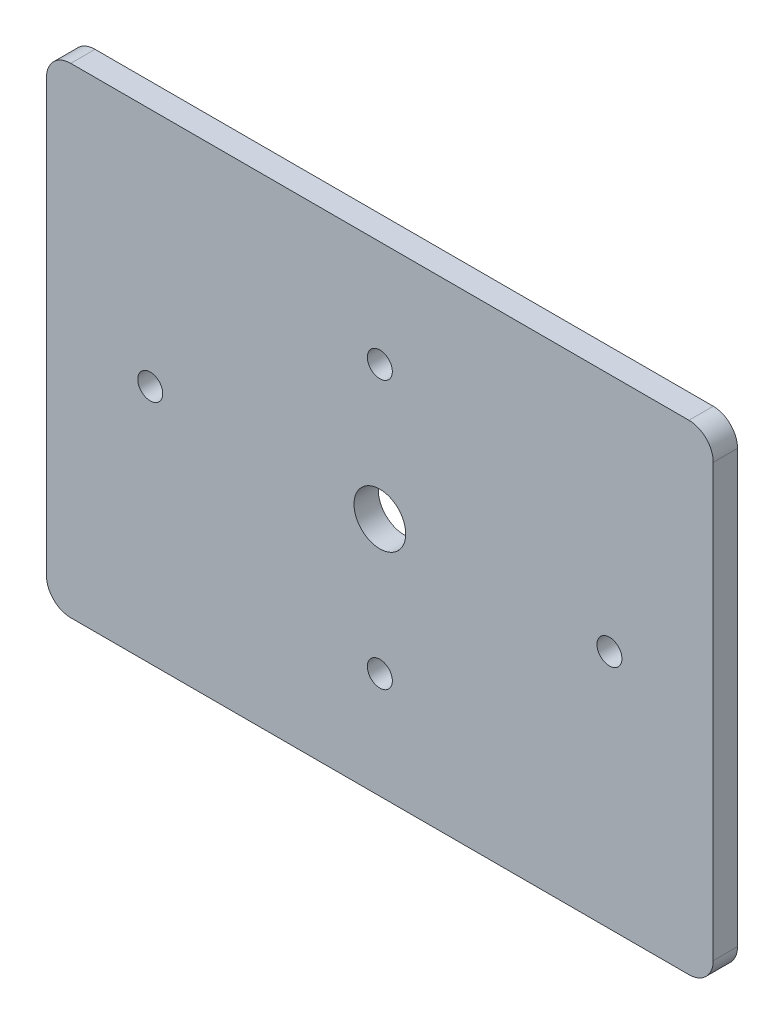
SolidWorks part; units mm, degrees
material "Acrylic (Medium-high impact)"
ref_plane "Front Plane" through (0, 0, 0) normal (0, 0, 1) x (1, 0, 0)
ref_plane "Top Plane" through (0, 0, 0) normal (0, 1, 0) x (1, 0, 0)
ref_plane "Right Plane" through (0, 0, 0) normal (1, 0, 0) x (0, 0, -1)
sketch "Sketch1" plane through (0, 0, 0) normal (0, 0, 1) x (1, 0, 0)
  line L1 (0, 0) -> (87.122, 0)
  line L2 (0, 0) -> (0, 62.738)
  line L3 (0, 62.738) -> (87.122, 62.738)
  line L4 (87.122, 0) -> (87.122, 62.738)
  dimension "D1" = 62.738
  dimension "D2" = 87.122
extrude "Boss-Extrude1" add sketch "Sketch1" along normal blind 3.175
hole_wizard "#4 Clearance Hole1" positions "Sketch2" profile "Sketch3" hole size "#4" standard "ANSI Inch" end condition through all
sketch "Sketch2" plane through (0, 0, 3.175) normal (0, 0, 1) x (1, 0, 0)
  line L0 (0, 62.738) -> (87.122, 0) construction
  line L2 (43.561, 31.369) -> (73.561, 31.369) construction
  line L3 (43.561, 31.369) -> (13.561, 31.369) construction
  line L4 (43.561, 31.369) -> (43.561, 48.869) construction
  line L5 (43.561, 31.369) -> (43.561, 13.869) construction
  point P9 (73.561, 31.369)
  point P12 (13.561, 31.369)
  point P14 (43.561, 48.869)
  point P17 (43.561, 13.869)
  dimension "D1" = 60
  dimension "D2" = 35
sketch "Sketch3" plane through (43.561, 13.869, 3.175) normal (1, 0, 0) x (0, -1, 0)
  line L0 (0, 0) -> (0, 3.175)
  line L1 (0, 3.175) -> (1.6319, 3.175)
  line L2 (1.6319, 3.175) -> (1.6319, 0)
  line L5 (1.6319, 0) -> (0, 0)
  line L11 (0, -6.35) -> (0, 107.95) construction
  dimension "Thru Hole Dia." = 3.2639
  dimension "Thru Hole Depth" = 3.175
hole_wizard "1/4 Clearance Hole1" positions "Sketch7" profile "Sketch8" hole size "1/4" standard "ANSI Inch" end condition through all
sketch "Sketch7" plane through (0, 0, 3.175) normal (0, 0, 1) x (1, 0, 0)
  line L0 (0, 62.738) -> (87.122, 0) construction
  point P6 (43.561, 31.369)
sketch "Sketch8" plane through (43.561, 31.369, 3.175) normal (1, 0, 0) x (0, -1, 0)
  line L0 (0, 0) -> (0, 3.175)
  line L1 (0, 3.175) -> (3.3782, 3.175)
  line L2 (3.3782, 3.175) -> (3.3782, 0)
  line L5 (3.3782, 0) -> (0, 0)
  line L11 (0, -6.35) -> (0, 107.95) construction
  dimension "Thru Hole Dia." = 6.7564
  dimension "Thru Hole Depth" = 3.175
fillet "Fillet1" radius 3.175 4 edges at (0, 62.738, 1.5875) (0, 0, 1.5875) (87.122, 0, 1.5875) (87.122, 62.738, 1.5875)
